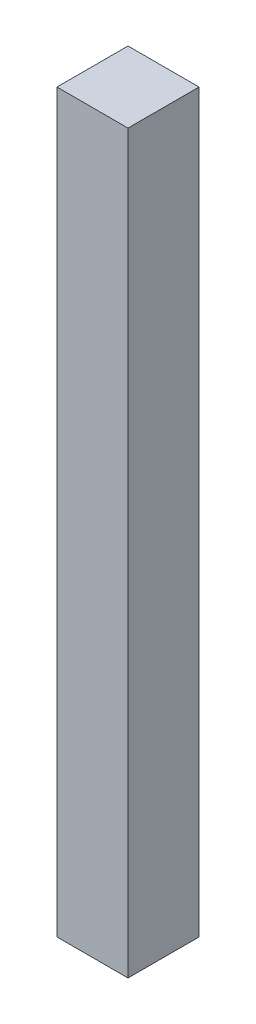
SolidWorks part; units mm, degrees
ref_plane "Alzado" through (0, 0, 0) normal (0, 0, 1) x (1, 0, 0)
ref_plane "Planta" through (0, 0, 0) normal (0, 1, 0) x (1, 0, 0)
ref_plane "Vista lateral" through (0, 0, 0) normal (1, 0, 0) x (0, 0, -1)
sketch "Croquis_pata" plane through (0, 0, 0) normal (0, 1, 0) x (1, 0, 0)
  line L1 (-35, -35) -> (35, -35)
  line L2 (-35, -35) -> (-35, 35)
  line L3 (-35, 35) -> (35, 35)
  line L4 (35, -35) -> (35, 35)
  line L5 (-35, -35) -> (35, 35) construction
  line L6 (-35, 35) -> (35, -35) construction
  point P0 (0, 0)
  dimension "D1" = 35
extrude "Pata_70x70x725" add sketch "Croquis_pata" along normal blind 725
